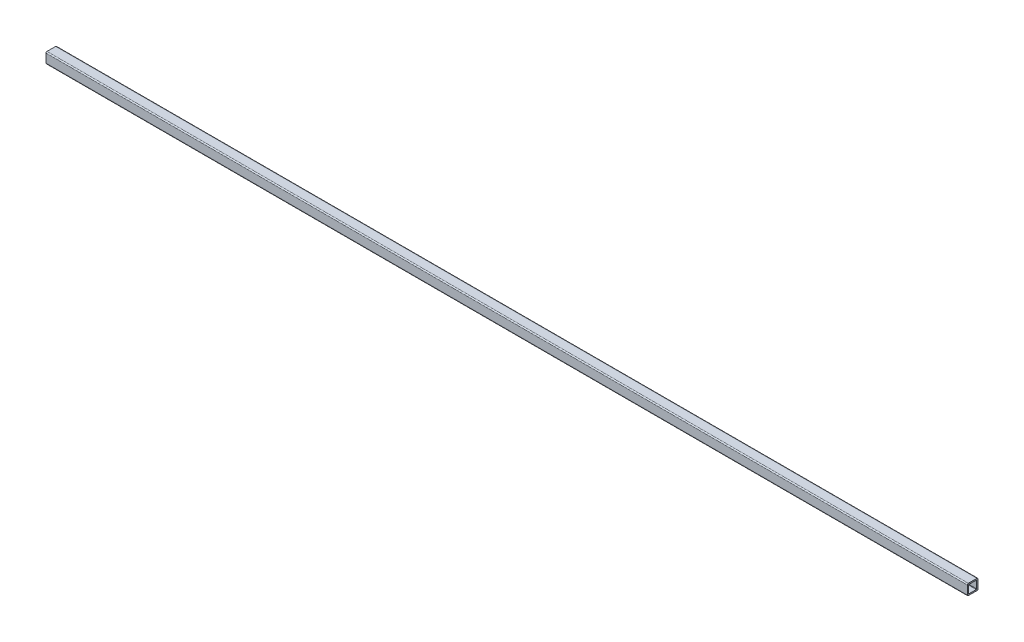
SolidWorks part; units mm, degrees
ref_plane "Front Plane" through (0, 0, 0) normal (0, 0, 1) x (1, 0, 0)
ref_plane "Top Plane" through (0, 0, 0) normal (0, 1, 0) x (1, 0, 0)
ref_plane "Right Plane" through (0, 0, 0) normal (1, 0, 0) x (0, 0, -1)
sketch "Sketch3" plane through (0, 0, 0) normal (1, 0, 0) x (0, 0, -1)
  line L1 (-12.7, 12.7) -> (12.7, 12.7)
  line L2 (-12.7, 12.7) -> (-12.7, -12.7)
  line L3 (-12.7, -12.7) -> (12.7, -12.7)
  line L4 (12.7, 12.7) -> (12.7, -12.7)
  line L5 (-12.7, 12.7) -> (12.7, -12.7) construction
  line L6 (-12.7, -12.7) -> (12.7, 12.7) construction
  line L7 (-9.652, -9.652) -> (9.652, -9.652)
  line L8 (-9.652, -9.652) -> (-9.652, 9.652)
  line L9 (-9.652, 9.652) -> (9.652, 9.652)
  line L10 (9.652, -9.652) -> (9.652, 9.652)
  line L11 (-9.652, -9.652) -> (9.652, 9.652) construction
  line L12 (-9.652, 9.652) -> (9.652, -9.652) construction
  point P0 (0, 0)
  point P6 (0, 0)
  dimension "D1" = 25.4
  dimension "D2" = 19.304
  dimension "D3" = 19.304
  dimension "D4" = 25.4
extrude "Boss-Extrude1" add sketch "Sketch3" against normal blind 2185.66
fillet "Fillet1" radius 2.5 4 edges at (-1092.83, -12.7, -12.7) (-1092.83, -12.7, 12.7) (-1092.83, 12.7, -12.7) (-1092.83, 12.7, 12.7)
fillet "Fillet2" radius 1 4 edges at (-1092.83, -9.652, -9.652) (-1092.83, 9.652, -9.652) (-1092.83, 9.652, 9.652) (-1092.83, -9.652, 9.652)
